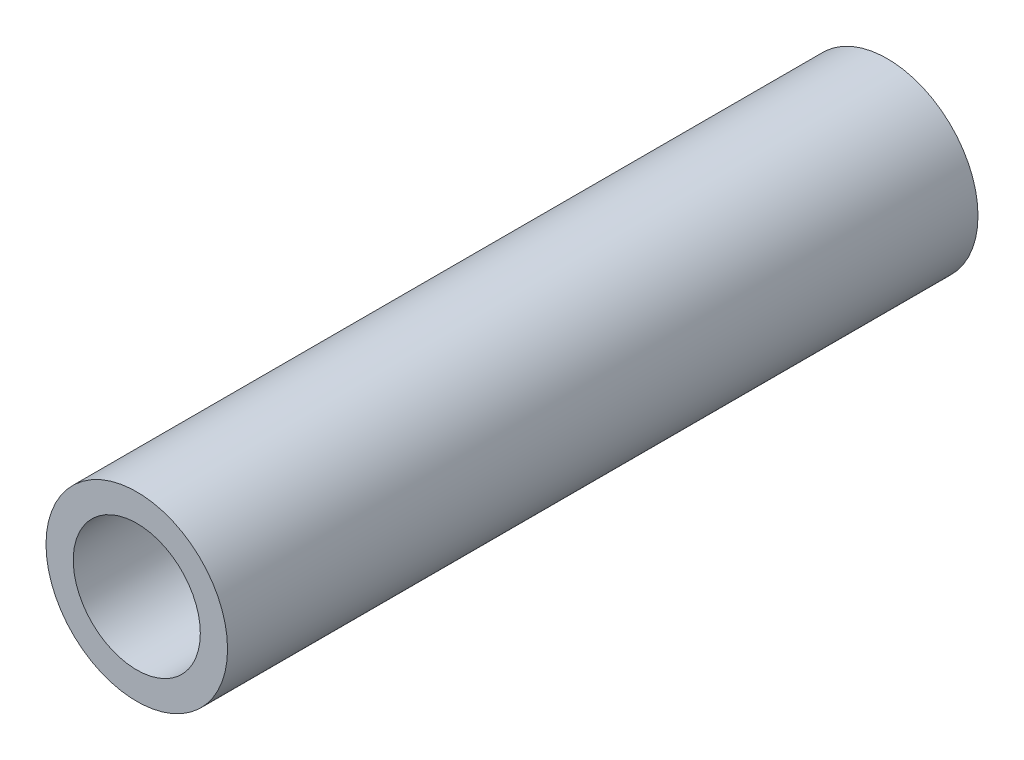
SolidWorks part; units mm, degrees
ref_plane "Alzado" through (0, 0, 0) normal (0, 0, 1) x (1, 0, 0)
ref_plane "Planta" through (0, 0, 0) normal (0, 1, 0) x (1, 0, 0)
ref_plane "Vista lateral" through (0, 0, 0) normal (1, 0, 0) x (0, 0, -1)
sketch "Croquis1" plane through (0, 0, 0) normal (0, 0, 1) x (1, 0, 0)
  circle A0 centre (0, 0) radius 2.625
  circle A1 centre (0, 0) radius 3.75
  dimension "D1" = 7.5
  dimension "D2" = 5.25
extrude "Saliente-Extruir1" add sketch "Croquis1" against normal blind 31
